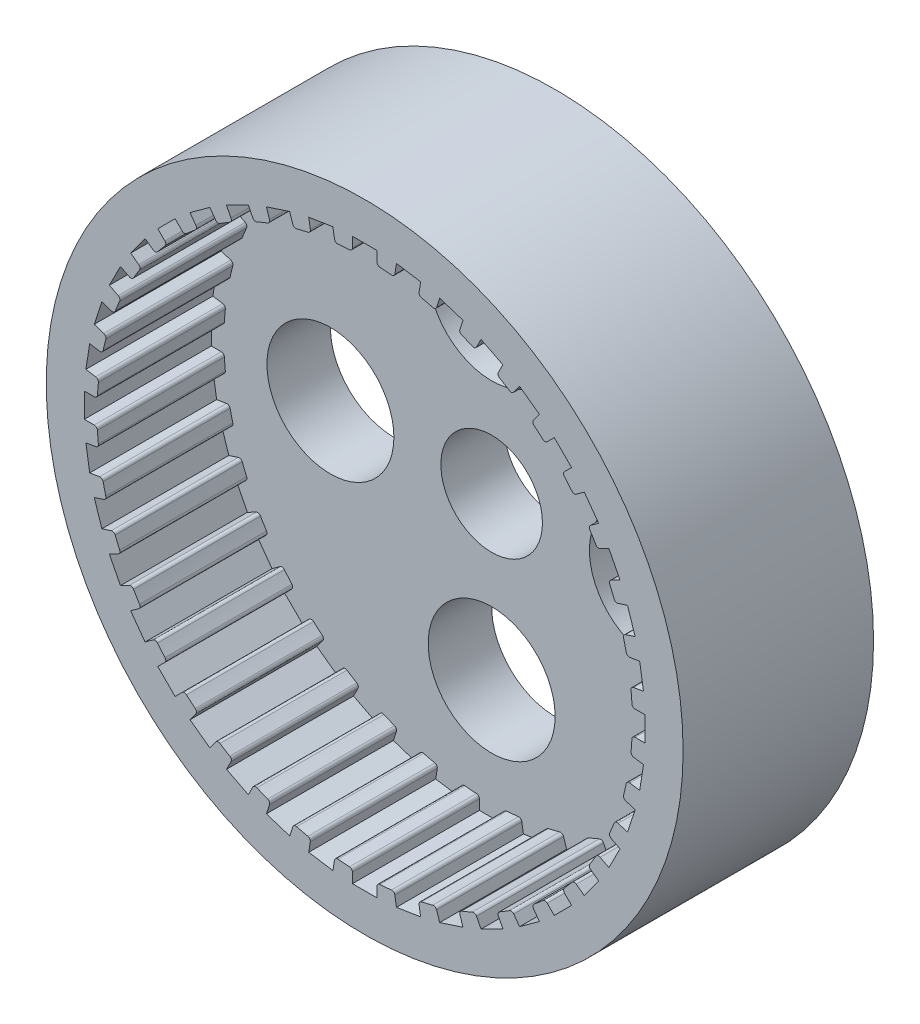
SolidWorks part; units mm, degrees
ref_plane "Front Plane" through (0, 0, 0) normal (0, 0, 1) x (1, 0, 0)
ref_plane "Top Plane" through (0, 0, 0) normal (0, 1, 0) x (1, 0, 0)
ref_plane "Right Plane" through (0, 0, 0) normal (1, 0, 0) x (0, 0, -1)
sketch "Sketch1" plane through (0, 0, 0) normal (0, 0, 1) x (1, 0, 0)
  circle A0 centre (0, 0) radius 21.082 construction
  point P3 (0, 0)
  point P11 (0, 0)
  point P12 (0, 0)
  dimension "D1" = 42.164
sketch "Sketch2" plane through (0, 0, 0) normal (0, 0, 1) x (1, 0, 0)
  circle A0 centre (0, 0) radius 25.082
  circle A1 centre (0, 0) radius 21.082 construction
  dimension "D1" = 4
extrude "Boss-Extrude1" add sketch "Sketch2" against normal blind 5
sketch "Sketch4" plane through (0, 0, 0) normal (0, 0, 1) x (1, 0, 0)
  circle A0 centre (0, 0) radius 25.082
  circle A1 centre (0, 0) radius 21.082
extrude "Boss-Extrude3" add sketch "Sketch4" along normal blind 10
sketch "Sketch3" plane through (0, 0, 0) normal (0, 0, 1) x (1, 0, 0)
  line L0 (0, 0) -> (0, 22.082) construction
  line L1 (-0.9641, 22.082) -> (0.9641, 22.082)
  line L2 (-0.9641, 22.082) -> (-0.9641, 21.0599)
  line L3 (-0.9641, 21.0599) -> (0.9641, 21.0599)
  line L4 (0.9641, 22.082) -> (0.9641, 21.0599)
  line L5 (0, 0) -> (-0.9641, 22.082) construction
  line L6 (0, 0) -> (0.9641, 22.082) construction
  circle A0 centre (0, 0) radius 21.082 construction
  circle A1 centre (0, 0) radius 22.082 construction
  point P2 (0, 0)
  point P10 (0, 21.0599)
  dimension "D1" = 42.164
  dimension "D2" = 1
  dimension "D3" = 5
extrude "Cut-Extrude1" cut sketch "Sketch3" along normal up to next
sketch "Sketch5" plane through (0, 0, 0) normal (0, 1, 0) x (1, 0, 0)
  line L0 (0, 0) -> (0, -43.4385) construction
fillet "Fillet1" radius 0.25 2 edges at (0.9641, 21.0599, 5) (-0.9641, 21.0599, 5)
pattern_circular "CirPattern1" count 40 over 360 about axis through (0, 0, 0) along (0, 0, 1) of "Cut-Extrude1", "Fillet1"
sketch "Sketch6" plane through (0, 0, -5) normal (0, 0, -1) x (-1, 0, 0)
  line L0 (0, 0) -> (0, 12.7) construction
  circle A1 centre (0, 12.7) radius 5
  dimension "D1" = 12.7
  dimension "D2" = 10
extrude "Cut-Extrude2" cut sketch "Sketch6" against normal through all both and the other way through all
pattern_circular "CirPattern2" count 4 over 360 about axis through (0, 0, 0) along (0, 0, 1) of "Cut-Extrude2"
sketch "Sketch7" plane through (0, 0, -5) normal (0, 0, -1) x (-1, 0, 0)
  circle A0 centre (0, 0) radius 4
  dimension "D1" = 8
extrude "Cut-Extrude3" cut sketch "Sketch7" against normal through all both and the other way through all
